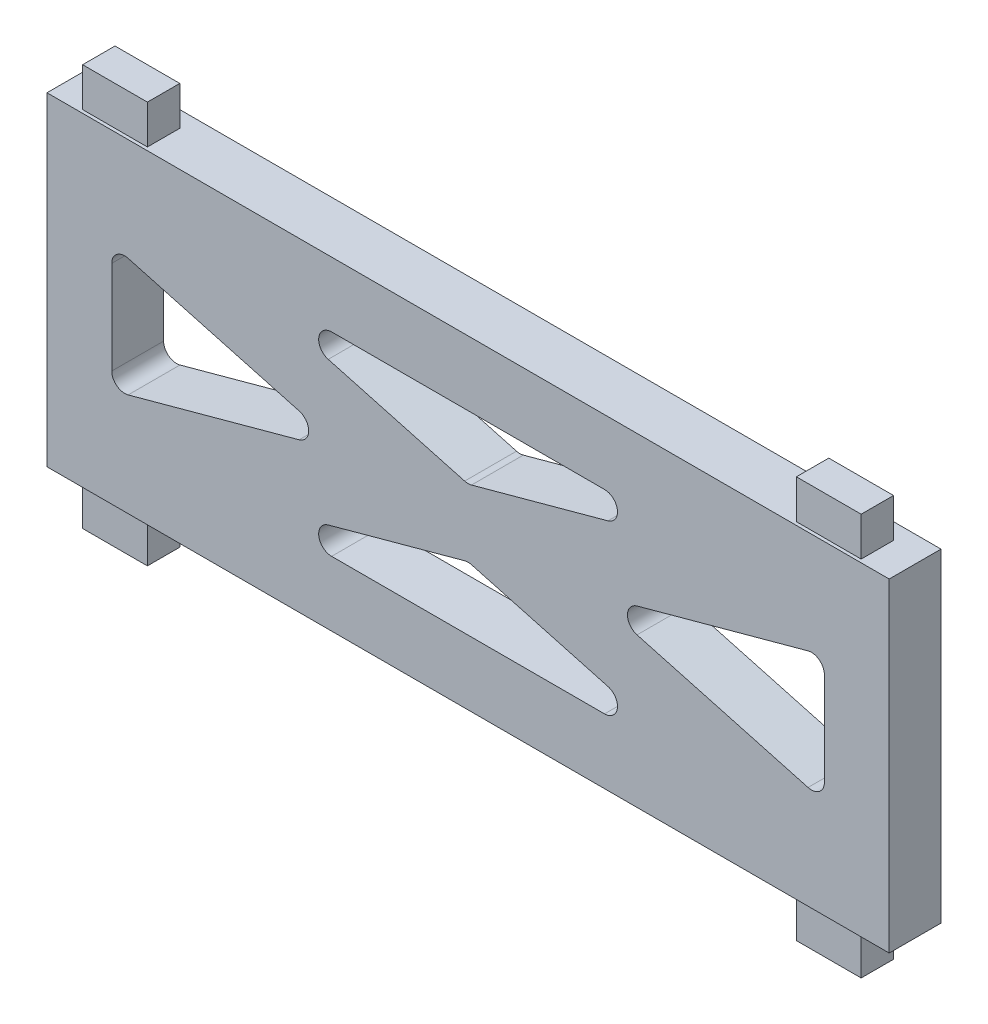
SolidWorks part; units mm, degrees
ref_plane "Front Plane" through (0, 0, 0) normal (0, 0, 1) x (1, 0, 0)
ref_plane "Top Plane" through (0, 0, 0) normal (0, 1, 0) x (1, 0, 0)
ref_plane "Right Plane" through (0, 0, 0) normal (1, 0, 0) x (0, 0, -1)
sketch "Sketch1" plane through (0, 0, 0) normal (0, 1, 0) x (1, 0, 0)
  line L0 (-84.0829, -32.8912) -> (-94.0829, -37.8912) construction
  line L1 (-84.0829, -37.8912) -> (-94.0829, -32.8912) construction
  line L2 (-33.9965, -40.3912) -> (-33.9965, -35.3912) construction
  line L3 (-33.9965, -30.3912) -> (-33.9965, -40.3912) construction
  line L4 (16.0899, -37.8912) -> (26.0899, -37.8912)
  line L5 (16.0899, -37.8912) -> (16.0899, -32.8912)
  line L6 (16.0899, -32.8912) -> (26.0899, -32.8912)
  line L7 (26.0899, -37.8912) -> (26.0899, -32.8912)
  line L8 (-94.0829, -37.8912) -> (-94.0829, -32.8912)
  line L9 (-84.0829, -32.8912) -> (-94.0829, -32.8912)
  line L10 (-84.0829, -37.8912) -> (-84.0829, -32.8912)
  line L11 (-84.0829, -37.8912) -> (-94.0829, -37.8912)
  point P11 (-89.0829, -35.3912)
extrude "Boss-Extrude1" add sketch "Sketch1" along normal blind 6
sketch "Sketch2" plane through (0, 6, 0) normal (0, 1, 0) x (1, 0, 0)
  line L1 (-99.0829, -30.3912) -> (30.9171, -30.3912)
  line L2 (-99.0829, -30.3912) -> (-99.0829, -38.3912)
  line L3 (-99.0829, -38.3912) -> (30.9171, -38.3912)
  line L4 (30.9171, -30.3912) -> (30.9171, -38.3912)
  line L5 (-84.0829, -32.8912) -> (-94.0829, -32.8912) construction
  line L6 (-94.0829, -32.8912) -> (-94.0829, -37.8912) construction
  dimension "D1" = 130
  dimension "D2" = 8
  dimension "D3" = 2.5
  dimension "D4" = 5
extrude "Boss-Extrude2" add sketch "Sketch2" along normal blind 50
sketch "Sketch3" plane through (0, 56, 0) normal (0, 1, 0) x (1, 0, 0)
  line L1 (-84.0829, -32.8912) -> (-94.0829, -32.8912)
  line L2 (-84.0829, -32.8912) -> (-84.0829, -37.8912)
  line L3 (-84.0829, -37.8912) -> (-94.0829, -37.8912)
  line L7 (-94.0829, -32.8912) -> (-94.0829, -37.8912)
  line L12 (16.0899, -32.8912) -> (26.0899, -32.8912)
  line L13 (16.0899, -32.8912) -> (16.0899, -37.8912)
  line L14 (16.0899, -37.8912) -> (26.0899, -37.8912)
  line L15 (26.0899, -32.8912) -> (26.0899, -37.8912)
extrude "Boss-Extrude3" add sketch "Sketch3" along normal blind 6
sketch "Sketch4" plane through (0, 0, 38.3912) normal (0, 0, 1) x (1, 0, 0)
  line L0 (-13.0203, 46) -> (-55.1454, 46)
  line L1 (-89.0829, 38.1989) -> (-89.0829, 23.8011)
  line L2 (-55.1454, 16) -> (-13.0203, 16)
  line L3 (20.9171, 23.8011) -> (20.9171, 38.1989)
  line L4 (-99.0829, 6) -> (30.9171, 6)
  line L5 (30.9171, 6) -> (30.9171, 56)
  line L6 (30.9171, 56) -> (-99.0829, 56)
  line L7 (-99.0829, 56) -> (-99.0829, 6)
  line L8 (-99.0829, 6) -> (30.9171, 6)
  line L9 (30.9171, 6) -> (30.9171, 56)
  line L10 (30.9171, 56) -> (-80.7214, 56)
  line L11 (-99.0829, 56) -> (-99.0829, 6)
  line L14 (-86.5566, 40.1284) -> (-60.1607, 32.9295)
  line L15 (-12.494, 42.0705) -> (-33.5566, 36.3261)
  line L16 (-55.6717, 42.0705) -> (-34.6091, 36.3261)
  line L17 (18.3909, 40.1284) -> (-8.005, 32.9295)
  line L19 (20.9171, 46) -> (-89.0829, 46) construction
  line L21 (20.9171, 16) -> (20.9171, 46) construction
  line L22 (-8.005, 29.0705) -> (18.3909, 21.8716)
  line L24 (-60.1607, 29.0705) -> (-86.5566, 21.8716)
  line L26 (-33.5566, 25.6739) -> (-12.494, 19.9295)
  line L28 (-89.0829, 16) -> (20.9171, 16) construction
  line L30 (-89.0829, 46) -> (-89.0829, 16) construction
  line L31 (30.9171, 56) -> (-99.0829, 56) construction
  line L32 (-34.6091, 25.6739) -> (-55.6717, 19.9295)
  arc A0 (-55.6717, 42.0705) -> (-55.1454, 46) centre (-55.1454, 44) cw
  arc A1 (-12.494, 42.0705) -> (-13.0203, 46) centre (-13.0203, 44) ccw
  arc A2 (-33.5566, 36.3261) -> (-34.6091, 36.3261) centre (-34.0829, 38.2557) cw
  arc A3 (-8.005, 29.0705) -> (-8.005, 32.9295) centre (-7.4788, 31) cw
  arc A4 (20.9171, 38.1989) -> (18.3909, 40.1284) centre (18.9171, 38.1989) ccw
  arc A5 (20.9171, 23.8011) -> (18.3909, 21.8716) centre (18.9171, 23.8011) cw
  arc A6 (-12.494, 19.9295) -> (-13.0203, 16) centre (-13.0203, 18) cw
  arc A7 (-33.5566, 25.6739) -> (-34.6091, 25.6739) centre (-34.0829, 23.7443) ccw
  arc A8 (-55.1454, 16) -> (-55.6717, 19.9295) centre (-55.1454, 18) cw
  arc A9 (-89.0829, 23.8011) -> (-86.5566, 21.8716) centre (-87.0829, 23.8011) ccw
  arc A10 (-89.0829, 38.1989) -> (-86.5566, 40.1284) centre (-87.0829, 38.1989) cw
  arc A11 (-60.1607, 29.0705) -> (-60.1607, 32.9295) centre (-60.6869, 31) ccw
  point P37 (-34.0829, 25.8174)
  dimension "D3" = 2
  dimension "D1" = 0
  dimension "D2" = 10
extrude "Cut-Extrude1" cut sketch "Sketch4" against normal through all contours L26 L32 L2 | L17 L22 L3 | L0 L16 L15 | L24 L14 L1
